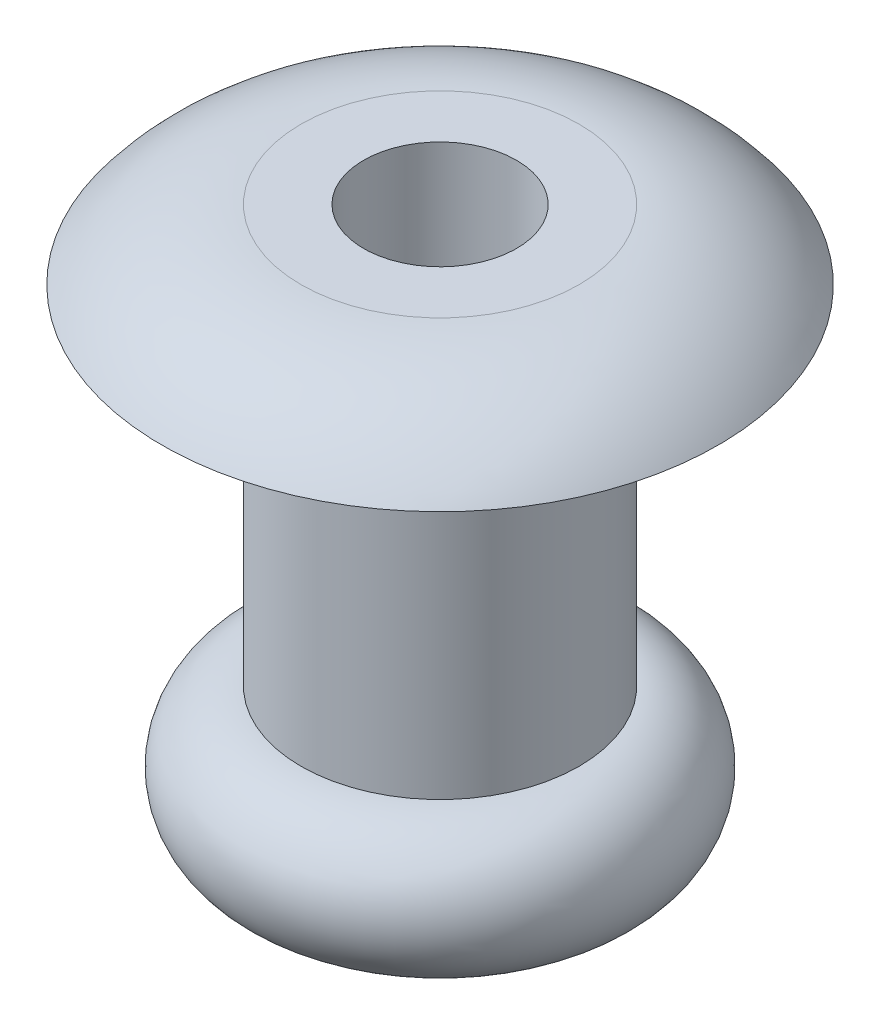
SolidWorks part; units mm, degrees
material "7050-T73510"
ref_plane "XZ" through (0, 0, 0) normal (0, 0, 1) x (1, 0, 0)
ref_plane "XY" through (0, 0, 0) normal (0, 1, 0) x (1, 0, 0)
ref_plane "YZ" through (0, 0, 0) normal (1, 0, 0) x (0, 0, -1)
sketch "Эскиз1" plane through (0, 0, 0) normal (0, 0, 1) x (1, 0, 0)
  line L0 (0, -12.8378) -> (0, 4.6806) construction
  line L1 (1.1, 1) -> (2, 1)
  line L2 (4, 0) -> (2, 0)
  line L3 (2, 0) -> (2, -5)
  line L4 (2, -10) -> (1.1, -10) construction
  line L5 (1.1, -7) -> (1.1, 1)
  line L6 (2, -7) -> (1.1, -7)
  line L7 (1.1, -7) -> (1.1, -10) construction
  line L8 (2, -5) -> (2, -10) construction
  arc A0 (2, 1) -> (4, 0) centre (2, -1.5) cw
  arc A1 (2, -5) -> (2, -7) centre (2, -6) cw
  dimension "D6" = 2.5
  dimension "D8" = 1
  dimension "D1" = 4
  dimension "D2" = 10
  dimension "D3" = 2.2
  dimension "D4" = 1
  dimension "D5" = 8
  dimension "D7" = 5
  dimension "D9" = 2
revolve "Повернуть1" add sketch "Эскиз1" angle 360 about L0
